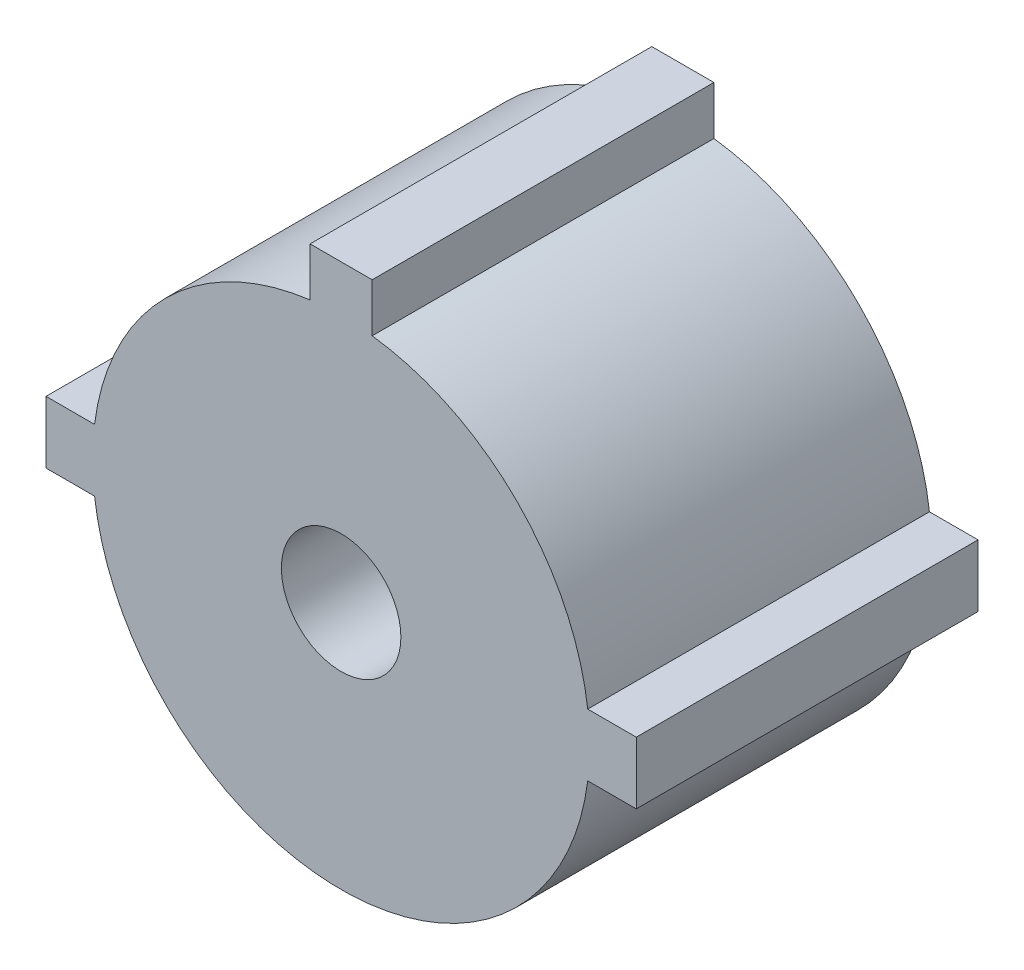
SolidWorks part; units mm, degrees
ref_plane "Front Plane" through (0, 0, 0) normal (0, 0, 1) x (1, 0, 0)
ref_plane "Top Plane" through (0, 0, 0) normal (0, 1, 0) x (1, 0, 0)
ref_plane "Right Plane" through (0, 0, 0) normal (1, 0, 0) x (0, 0, -1)
sketch "Sketch1" plane through (0, 0, 0) normal (0, 0, 1) x (1, 0, 0)
  line L1 (-4.75, 0.5) -> (4.75, 0.5)
  line L2 (-4.75, 0.5) -> (-4.75, -0.5)
  line L3 (-4.75, -0.5) -> (4.75, -0.5)
  line L4 (4.75, 0.5) -> (4.75, -0.5)
  line L5 (-4.75, 0.5) -> (4.75, -0.5) construction
  line L6 (-4.75, -0.5) -> (4.75, 0.5) construction
  line L7 (-0.5, 4.75) -> (0.5, 4.75)
  line L8 (-0.5, 4.75) -> (-0.5, -0.5)
  line L10 (0.5, 4.75) -> (0.5, -0.5)
  line L11 (-0.5, 4.75) -> (0.0526, -0.5) construction
  line L13 (-0.0519, -0.5) -> (0.5, 4.75) construction
  circle A0 centre (0, 0) radius 4
  circle A1 centre (0, 0) radius 0.9616
  dimension "D1" = 1
  dimension "D2" = 1
  dimension "D3" = 9.5
  dimension "D4" = 5.25
extrude "Boss-Extrude1" add sketch "Sketch1" along normal blind 5.5 contours A1 L3 A0 | A1 L8 A0 L1 | A1 L1 A0 L10 | A1 L1 A0 L3 | A1 L10 A0 L8 | A1 L3 A0 L1 | A0 L1 L2 L3 | A0 L3 L4 L1 | A0 L10 L7 L8
